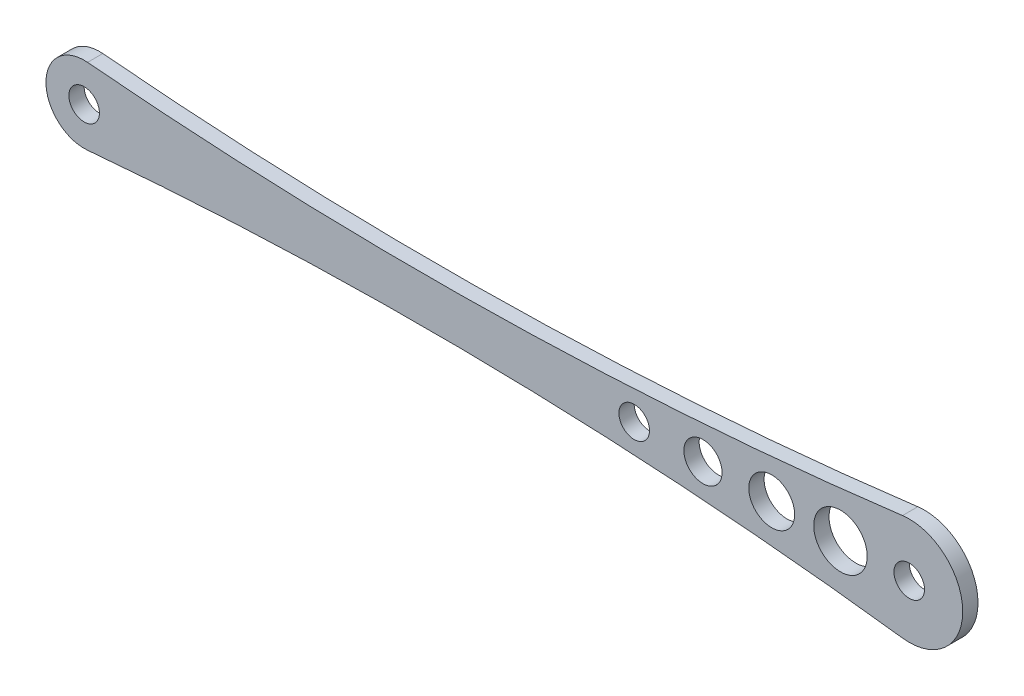
SolidWorks part; units mm, degrees
ref_plane "前视基准面" through (0, 0, 0) normal (0, 0, 1) x (1, 0, 0)
ref_plane "上视基准面" through (0, 0, 0) normal (0, 1, 0) x (1, 0, 0)
ref_plane "右视基准面" through (0, 0, 0) normal (1, 0, 0) x (0, 0, -1)
sketch "草图1" plane through (0, 0, 0) normal (0, 0, 1) x (1, 0, 0)
  line L0 (0, 0) -> (54, 0) construction
  circle A0 centre (0, 0) radius 1
  circle A1 centre (54, 0) radius 1
  arc A2 (0.2232, 2.49) -> (0.2232, -2.49) centre (0, 0) ccw
  arc A3 (53.5594, -3.4722) -> (53.5594, 3.4722) centre (54, 0) ccw
  arc A4 (0.2232, 2.49) -> (53.5594, 3.4722) centre (22.3544, 249.3604) ccw
  arc A5 (0.2232, -2.49) -> (53.5594, -3.4722) centre (22.3544, -249.3604) cw
  circle A6 centre (49.5, 0) radius 1.75
  circle A7 centre (45, 0) radius 1.5
  circle A8 centre (40.5, 0) radius 1.25
  circle A9 centre (36, 0) radius 1
  dimension "D1" = 2
  dimension "D3" = 7
  dimension "D4" = 5
  dimension "D5" = 3
  dimension "D10" = 3.5
  dimension "D11" = 3
  dimension "D12" = 2.5
  dimension "D13" = 2
  dimension "D2" = 54
  dimension "D6" = 4.5
  dimension "D7" = 4.5
  dimension "D8" = 4.5
  dimension "D9" = 4.5
extrude "凸台-拉伸1" add sketch "草图1" along normal blind 1
